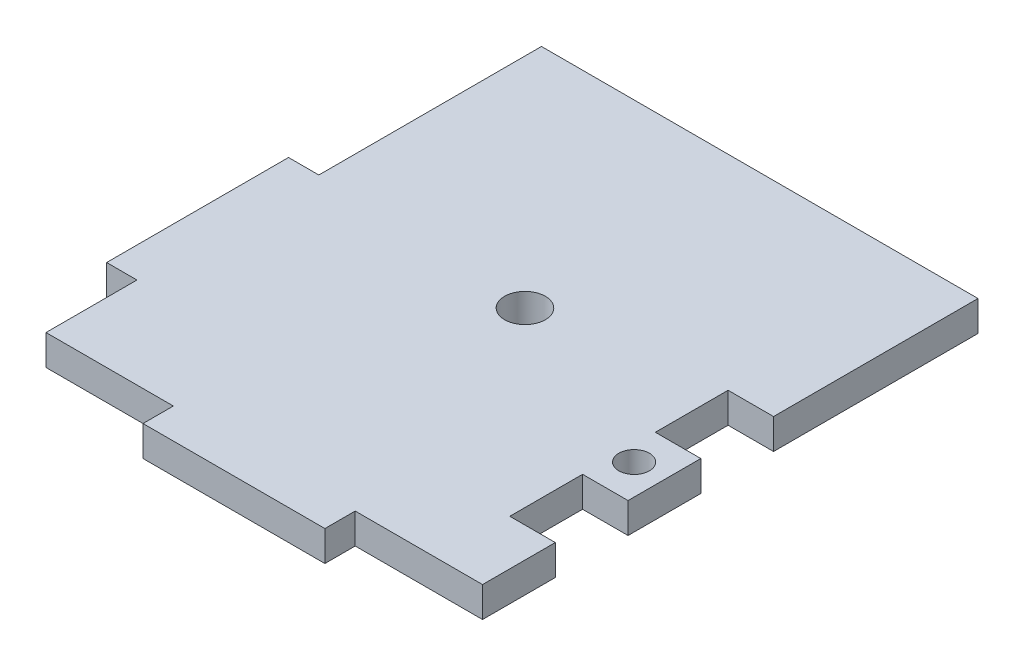
SolidWorks part; units mm, degrees
ref_plane "Front Plane" through (0, 0, 0) normal (0, 0, 1) x (1, 0, 0)
ref_plane "Top Plane" through (0, 0, 0) normal (0, 1, 0) x (1, 0, 0)
ref_plane "Right Plane" through (0, 0, 0) normal (1, 0, 0) x (0, 0, -1)
sketch "Sketch1" plane through (0, 0, 0) normal (0, 1, 0) x (1, 0, 0)
  line L0 (0, 0) -> (13.335, 0)
  line L1 (13.335, 0) -> (13.335, -3.175)
  line L2 (13.335, -3.175) -> (32.385, -3.175)
  line L3 (32.385, -3.175) -> (32.385, 0)
  line L4 (32.385, 0) -> (45.72, 0)
  line L5 (45.72, 0) -> (45.72, 7.62)
  line L10 (45.72, 51.8922) -> (0, 51.8922)
  line L11 (0, 51.8922) -> (0, 28.575)
  line L12 (0, 28.575) -> (-3.175, 28.575)
  line L13 (-3.175, 28.575) -> (-3.175, 9.525)
  line L14 (-3.175, 9.525) -> (0, 9.525)
  line L15 (0, 9.525) -> (0, 0)
  line L16 (45.72, 15.24) -> (45.72, 22.86)
  line L17 (40.9575, 30.48) -> (45.72, 30.48)
  line L18 (40.9575, 30.48) -> (40.9575, 22.86)
  line L19 (40.9575, 22.86) -> (45.72, 22.86)
  line L20 (45.72, 30.48) -> (45.72, 51.8922)
  line L21 (40.9575, 15.24) -> (45.72, 15.24)
  line L22 (40.9575, 15.24) -> (40.9575, 7.62)
  line L23 (40.9575, 7.62) -> (45.72, 7.62)
  dimension "D2" = 19.05
  dimension "D3" = 19.05
  dimension "D4" = 45.72
  dimension "D5" = 51.8922
  dimension "D6" = 9.525
  dimension "D7" = 4.7625
  dimension "D8" = 7.62
  dimension "D9" = 7.62
  dimension "D10" = 7.62
  dimension "D11" = 7.62
  dimension "D12" = 3.175
extrude "Boss-Extrude1" add sketch "Sketch1" along normal blind 3.175
hole_wizard "M3 Clearance Hole1" positions "Sketch3" profile "Sketch2" hole size "M3" standard "ANSI Metric" end condition through all
sketch "Sketch3" plane through (0, 3.175, 0) normal (0, 1, 0) x (1, 0, 0)
  line L3 (42.545, 22.86) -> (42.545, 15.24) construction
  line L4 (45.72, 22.86) -> (40.9575, 22.86) construction
  line L5 (40.9575, 15.24) -> (45.72, 15.24) construction
  line L8 (40.9575, 22.86) -> (40.9575, 30.48) construction
  point P0 (42.545, 19.05)
  point P21 (42.545, 19.05)
  dimension "D1" = 1.5875
sketch "Sketch2" plane through (42.545, 3.175, -19.05) normal (1, 0, 0) x (0, 0, 1)
  line L0 (0, 0) -> (0, 3.175)
  line L1 (0, 3.175) -> (1.6, 3.175)
  line L2 (1.6, 3.175) -> (1.6, 0)
  line L5 (1.6, 0) -> (0, 0)
  line L11 (0, -6.35) -> (0, 107.95) construction
  dimension "Thru Hole Dia." = 3.2
  dimension "Thru Hole Depth" = 3.175
sketch "Sketch4" plane through (0, 3.175, 0) normal (0, 1, 0) x (1, 0, 0)
  line L0 (13.335, -3.175) -> (32.385, -3.175) construction
  line L1 (22.86, 27.305) -> (22.86, -3.175) construction
  circle A0 centre (22.86, 27.305) radius 2.1336
  dimension "D1" = 4.2672
  dimension "D2" = 30.48
extrude "Cut-Extrude1" cut sketch "Sketch4" against normal through all
